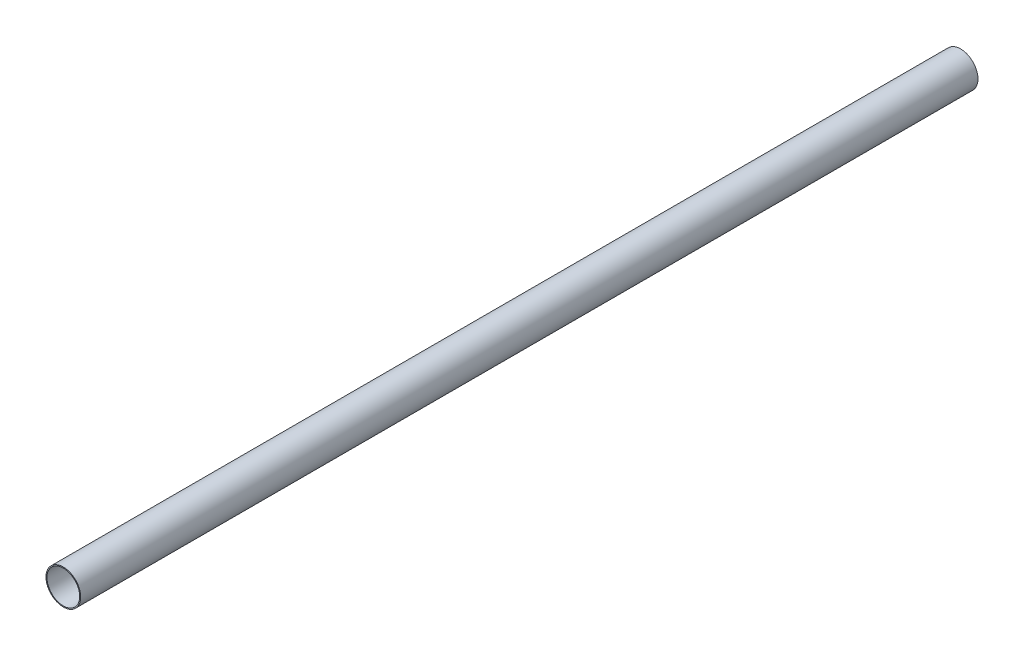
SolidWorks part; units mm, degrees
material "Thornel Mat VMA"
ref_plane "Front" through (0, 0, 0) normal (0, 0, 1) x (1, 0, 0)
ref_plane "Top" through (0, 0, 0) normal (0, 1, 0) x (1, 0, 0)
ref_plane "Right" through (0, 0, 0) normal (1, 0, 0) x (0, 0, -1)
sketch "Sketch1" plane through (0, 0, 0) normal (0, 0, 1) x (1, 0, 0)
  circle A0 centre (0, 0) radius 22.1107
  circle A1 centre (0, 0) radius 20.8407
  dimension "D1" = 44.2214
  dimension "D2" = 1.27
extrude "Boss-Extrude1" add sketch "Sketch1" along normal blind 1143
